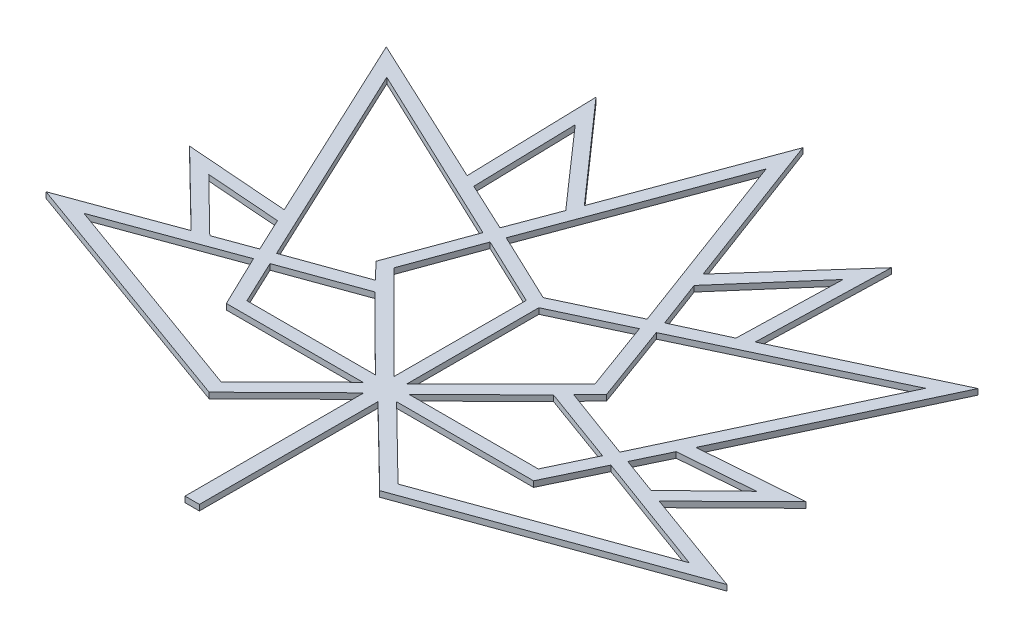
SolidWorks part; units mm, degrees
ref_plane "Front Plane" through (0, 0, 0) normal (0, 0, 1) x (1, 0, 0)
ref_plane "Top Plane" through (0, 0, 0) normal (0, 1, 0) x (1, 0, 0)
ref_plane "Right Plane" through (0, 0, 0) normal (1, 0, 0) x (0, 0, -1)
sketch "Sketch1" plane through (0, 0, 0) normal (0, 1, 0) x (1, 0, 0)
  line L0 (266, 833.5) -> (1330, 833.5) construction
  line L1 (784.9879, 398.0072) -> (785.0006, 709.0007)
  line L2 (785.0006, 709.0007) -> (783.999, 709.0007)
  line L3 (783.999, 709.0007) -> (648.9543, 576.0063)
  line L4 (648.9543, 576.0063) -> (204.0129, 736.5155)
  line L5 (204.0129, 736.5155) -> (389.3468, 804.3821)
  line L6 (389.3468, 804.3821) -> (260.2692, 930.5946)
  line L7 (260.2692, 930.5946) -> (438.9858, 917.0171)
  line L8 (438.9858, 917.0171) -> (281.9975, 1251.9945)
  line L9 (281.9975, 1251.9945) -> (546.9971, 1127.9983)
  line L10 (546.9971, 1127.9983) -> (540.8203, 1358.9424)
  line L11 (540.8203, 1358.9424) -> (694.4847, 1184.9827)
  line L12 (694.4847, 1184.9827) -> (797.5272, 1462.9883)
  line L13 (797.5272, 1462.9883) -> (901.5079, 1184.9827)
  line L14 (901.5079, 1184.9827) -> (1055.9947, 1359.0076)
  line L15 (1055.9947, 1359.0076) -> (1049.4816, 1127.9983)
  line L16 (1049.4816, 1127.9983) -> (1313.9954, 1251.9945)
  line L17 (1313.9954, 1251.9945) -> (1156.9918, 916.995)
  line L18 (1156.9918, 916.995) -> (1334.9983, 930.9999)
  line L19 (1334.9983, 930.9999) -> (1205.9358, 803.9887)
  line L20 (1205.9358, 803.9887) -> (1391.0019, 736.9909)
  line L21 (1391.0019, 736.9909) -> (946.5595, 576.0063)
  line L22 (946.5595, 576.0063) -> (810.546, 709.0007)
  line L23 (810.546, 709.0007) -> (809.9872, 398.0072)
  line L24 (809.9872, 398.0072) -> (784.9879, 398.0072)
  line L25 (768.2114, 725.0317) -> (643.9926, 601.9603)
  line L26 (643.9926, 601.9603) -> (269.6794, 736.9909)
  line L27 (269.6794, 736.9909) -> (486.1229, 816.2494)
  line L28 (486.1229, 816.2494) -> (530.0473, 725.0317)
  line L29 (530.0473, 725.0317) -> (768.2114, 725.0317)
  line L30 (826.9957, 725.0317) -> (952.5131, 601.9603)
  line L31 (952.5131, 601.9603) -> (1325.3022, 736.9909)
  line L32 (1325.3022, 736.9909) -> (1109.4673, 816.2494)
  line L33 (1109.4673, 816.2494) -> (1065.8313, 725.0317)
  line L34 (1065.8313, 725.0317) -> (826.9957, 725.0317)
  line L35 (826.9957, 747.0438) -> (1052.0546, 747.0438)
  line L36 (1052.0546, 747.0438) -> (1088.0543, 823.0647)
  line L37 (1088.0543, 823.0647) -> (953.48, 872.1264)
  line L38 (953.48, 872.1264) -> (826.9957, 747.0438)
  line L39 (767.9523, 747.0438) -> (543.9087, 747.0438)
  line L40 (543.9087, 747.0438) -> (507.9098, 823.3029)
  line L41 (507.9098, 823.3029) -> (642.1579, 871.9299)
  line L42 (642.1579, 871.9299) -> (767.9523, 747.0438)
  line L43 (476.9106, 836.3619) -> (413.1547, 813.0155)
  line L44 (413.1547, 813.0155) -> (319.8178, 904.5335)
  line L45 (319.8178, 904.5335) -> (449.5601, 894.6766)
  line L46 (449.5601, 894.6766) -> (476.9106, 836.3619)
  line L47 (1118.8309, 836.3619) -> (1182.8694, 813.0155)
  line L48 (1182.8694, 813.0155) -> (1276.1369, 903.6692)
  line L49 (1276.1369, 903.6692) -> (1146.1404, 893.4416)
  line L50 (1146.1404, 893.4416) -> (1118.8309, 836.3619)
  line L51 (809.006, 761) -> (973.1451, 924.8912)
  line L52 (973.1451, 924.8912) -> (928.3996, 1047.0847)
  line L53 (928.3996, 1047.0847) -> (809.006, 991.0874)
  line L54 (809.006, 991.0874) -> (809.006, 761)
  line L55 (786.5817, 761) -> (786.9951, 991.0874)
  line L56 (786.9951, 991.0874) -> (667.2159, 1047.8088)
  line L57 (667.2159, 1047.8088) -> (622.4039, 924.8912)
  line L58 (622.4039, 924.8912) -> (786.5817, 761)
  line L59 (625.0712, 890.1001) -> (596.7535, 919.2342)
  line L60 (596.7535, 919.2342) -> (646.8619, 1055.6884)
  line L61 (646.8619, 1055.6884) -> (328.3656, 1206.5121)
  line L62 (328.3656, 1206.5121) -> (498.1649, 844.4777)
  line L63 (498.1649, 844.4777) -> (625.0712, 890.1001)
  line L64 (970.8901, 890.1001) -> (1097.7098, 843.5296)
  line L65 (1097.7098, 843.5296) -> (1267.8283, 1206.5121)
  line L66 (1267.8283, 1206.5121) -> (948.9468, 1055.9808)
  line L67 (948.9468, 1055.9808) -> (999.0214, 919.2342)
  line L68 (999.0214, 919.2342) -> (970.8901, 890.1001)
  line L69 (797.5272, 1010.0932) -> (920.7014, 1068.239)
  line L70 (920.7014, 1068.239) -> (797.5272, 1398.9023)
  line L71 (797.5272, 1398.9023) -> (674.9671, 1068.239)
  line L72 (674.9671, 1068.239) -> (797.5272, 1010.0932)
  line L73 (654.434, 1077.8907) -> (685.6642, 1161.3123)
  line L74 (685.6642, 1161.3123) -> (564.3658, 1299.116)
  line L75 (564.3658, 1299.116) -> (568.8572, 1117.8068)
  line L76 (568.8572, 1117.8068) -> (654.434, 1077.8907)
  line L77 (941.6133, 1077.8907) -> (1026.7421, 1116.969)
  line L78 (1026.7421, 1116.969) -> (1031.6766, 1299.116)
  line L79 (1031.6766, 1299.116) -> (910.7814, 1160.1234)
  line L80 (910.7814, 1160.1234) -> (941.6133, 1077.8907)
extrude "Boss-Extrude1" add sketch "Sketch1" along normal blind 10
